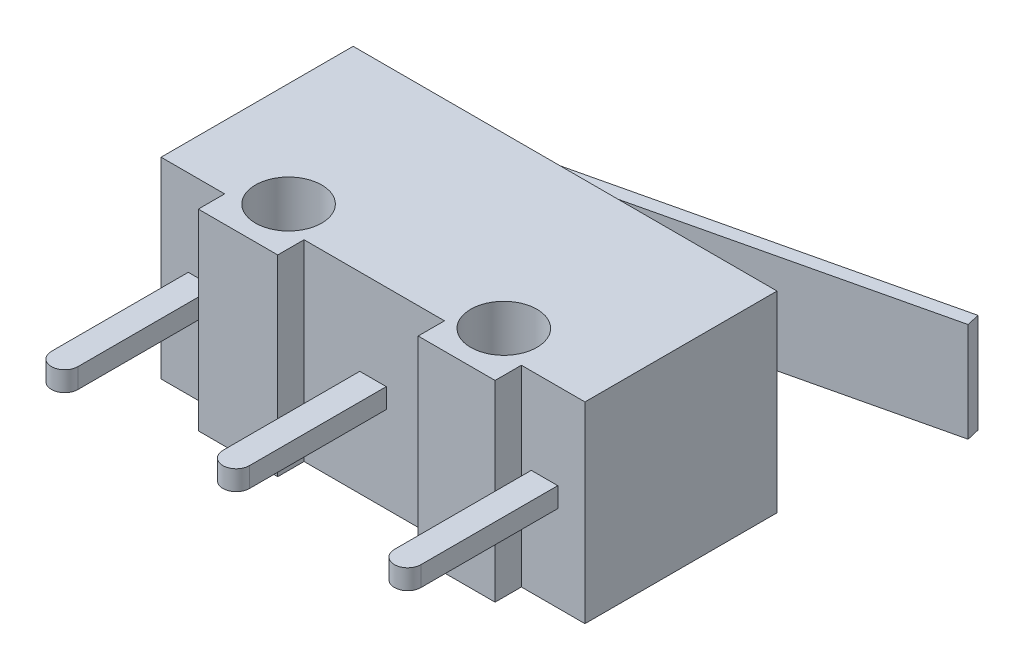
SolidWorks part; units mm, degrees
ref_plane "Front Plane" through (0, 0, 0) normal (0, 0, 1) x (1, 0, 0)
ref_plane "Top Plane" through (0, 0, 0) normal (0, 1, 0) x (1, 0, 0)
ref_plane "Right Plane" through (0, 0, 0) normal (1, 0, 0) x (0, 0, -1)
sketch "Sketch1" plane through (0, 0, 0) normal (0, 1, 0) x (1, 0, 0)
  line L0 (6.4, 0) -> (6.4, 5.8)
  line L1 (6.4, 5.8) -> (-6.4, 5.8)
  line L2 (-6.4, 5.8) -> (-6.4, 0)
  line L3 (-6.4, 0) -> (-4.4806, 0)
  line L4 (-4.4806, 0) -> (-4.4806, -0.795)
  line L5 (-4.4806, -0.795) -> (-2.0826, -0.795)
  line L6 (-2.0826, -0.795) -> (-2.0826, 0)
  line L7 (-2.0826, 0) -> (2.1579, 0)
  line L8 (2.1579, 0) -> (2.1579, -0.795)
  line L9 (2.1579, -0.795) -> (4.4806, -0.795)
  line L10 (4.4806, -0.795) -> (4.4806, 0)
  line L11 (4.4806, 0) -> (6.4, 0)
  line L12 (0, 0) -> (0, 0.7) construction
  line L13 (-3.25, 0.7) -> (3.25, 0.7) construction
  circle A0 centre (3.25, 0.7) radius 1
  circle A1 centre (-3.25, 0.7) radius 1
  point P19 (0, 0.7)
  point P20 (3.2956, 0.7152)
  point P21 (-6.2377, 5.8)
  point P22 (6.3541, 0)
  point P23 (-4.4675, -0.793)
  point P24 (0, 0)
  point P25 (2.0697, -0.8076)
  point P26 (4.5554, -0.8131)
  point P27 (6.4173, 0)
  point P28 (4.532, -0.7772)
  point P29 (2.1532, -0.8197)
  point P30 (3.431, 0.7152)
  point P31 (2.1174, 0)
  point P32 (-4.4425, -0.8058)
  point P33 (-2.0826, -0.795)
  point P34 (2.1579, -0.8045)
  point P35 (4.5152, 0)
  point P36 (3.2695, 0.7152)
  point P37 (0, 0.7)
  point P38 (0, 5.8)
  dimension "D3" = 2
  dimension "D6" = 2
  dimension "D1" = 5.8
  dimension "D2" = 12.8
  dimension "D4" = 5.1
  dimension "D5" = 6.5
extrude "Boss-Extrude1" add sketch "Sketch1" along normal blind 5.8
ref_plane "Plane1" through (0, 2.9, 0) normal (0, 1, 0) x (1, 0, 0)
sketch "Sketch2" plane through (0, 2.9, 0) normal (0, 1, 0) x (1, 0, 0)
  line L0 (8.7161, 9.4035) -> (-4.6694, 6.2626)
  line L1 (6.4, 5.8) -> (-6.4, 5.8) construction
  arc A0 (-4.6694, 6.2626) -> (-5.1017, 5.8) centre (-4.5391, 5.7075) ccw
  point P4 (8.6703, 9.4047)
  point P5 (-5.3424, 5.8)
  point P8 (-4.7216, 6.1866)
  point P9 (-5.1017, 5.8)
  point P10 (-4.6583, 6.3766)
  point P11 (8.7337, 9.3287)
extrude "Extrude-Thin1" add sketch "Sketch2" along normal mid plane 3 thin thin type mid plane wall 0.4
sketch "Sketch3" plane through (0, 2.9, 0) normal (0, 1, 0) x (1, 0, 0)
  line L0 (-5.579, 0) -> (-5.579, -4.1312)
  line L1 (-6.4, 0) -> (-4.4806, 0) construction
  line L2 (-4.779, -4.1312) -> (-4.779, 0)
  line L3 (-4.779, 0) -> (-5.579, 0)
  line L4 (0, 0) -> (0, -4.5312) construction
  line L5 (-0.4, -4.1312) -> (-0.4, 0)
  line L6 (-2.0826, 0) -> (2.1579, 0) construction
  line L7 (-0.4, 0) -> (0.4, 0)
  line L8 (0.4, -4.1312) -> (0.4, 0)
  line L9 (4.779, 0) -> (5.579, 0)
  line L10 (4.779, -4.1312) -> (4.779, 0)
  line L11 (5.579, 0) -> (5.579, -4.1312)
  arc A0 (-5.579, -4.1312) -> (-4.779, -4.1312) centre (-5.179, -4.1312) ccw
  arc A1 (0.4, -4.1312) -> (-0.4, -4.1312) centre (0, -4.1312) cw
  arc A2 (5.579, -4.1312) -> (4.779, -4.1312) centre (5.179, -4.1312) cw
  point P12 (-5.199, -4.1312)
  point P13 (-0.4457, -4.1281)
  point P17 (-4.779, 0)
  point P18 (0, 0)
  dimension "D1" = 0.8
  dimension "D2" = 0.4
extrude "Boss-Extrude2" add sketch "Sketch3" along normal mid plane 0.6
